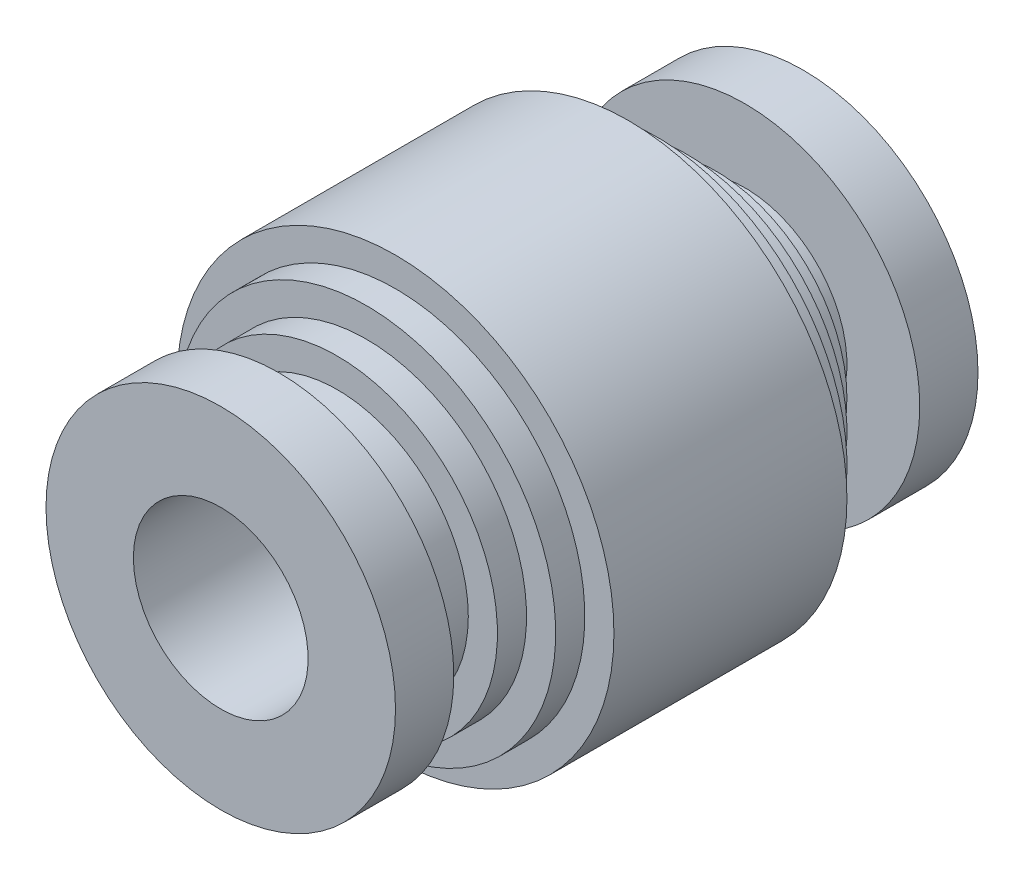
SolidWorks part; units mm, degrees
ref_plane "Спереди" through (0, 0, 0) normal (0, 0, 1) x (1, 0, 0)
ref_plane "Сверху" through (0, 0, 0) normal (0, 1, 0) x (1, 0, 0)
ref_plane "Справа" through (0, 0, 0) normal (1, 0, 0) x (0, 0, -1)
sketch "Эскиз1" plane through (0, 0, 0) normal (0, 1, 0) x (1, 0, 0)
  line L0 (5.5, 6) -> (4.5, 6)
  line L1 (5.5, 6) -> (5.5, 5)
  line L2 (5.5, 5) -> (6.5, 5)
  line L3 (6.5, 5) -> (6.5, 4)
  line L4 (6.5, 4) -> (7.5, 4)
  line L6 (0, 10) -> (0, -10) construction
  line L7 (0, 0) -> (7.5, 0) construction
  line L13 (0, 10) -> (0, -10)
  line L14 (3, 10) -> (3, -10)
  line L15 (4.5, 6) -> (4.5, 7)
  line L16 (4.5, 7) -> (3.5, 7)
  line L17 (3.5, 7) -> (3.5, 8)
  line L18 (3.5, 8) -> (6, 8)
  line L19 (6, 8) -> (6, 10)
  line L20 (6, 10) -> (0, 10)
  line L21 (7.5, 4) -> (7.5, -4)
  line L22 (6, -10) -> (0, -10)
  line L23 (6, -8) -> (6, -10)
  line L24 (3.5, -8) -> (6, -8)
  line L25 (3.5, -7) -> (3.5, -8)
  line L26 (4.5, -7) -> (3.5, -7)
  line L27 (4.5, -6) -> (4.5, -7)
  line L28 (6.5, -4) -> (7.5, -4)
  line L29 (6.5, -5) -> (6.5, -4)
  line L30 (5.5, -5) -> (6.5, -5)
  line L31 (5.5, -6) -> (5.5, -5)
  line L32 (5.5, -6) -> (4.5, -6)
  point P27 (3, 0)
  dimension "D1" = 7.5
  dimension "D2" = 6
  dimension "D3" = 4
  dimension "D4" = 1
  dimension "D5" = 2
  dimension "D6" = 6.5
  dimension "D7" = 3
revolve "Повернуть1" add sketch "Эскиз1" angle 360 about L13
